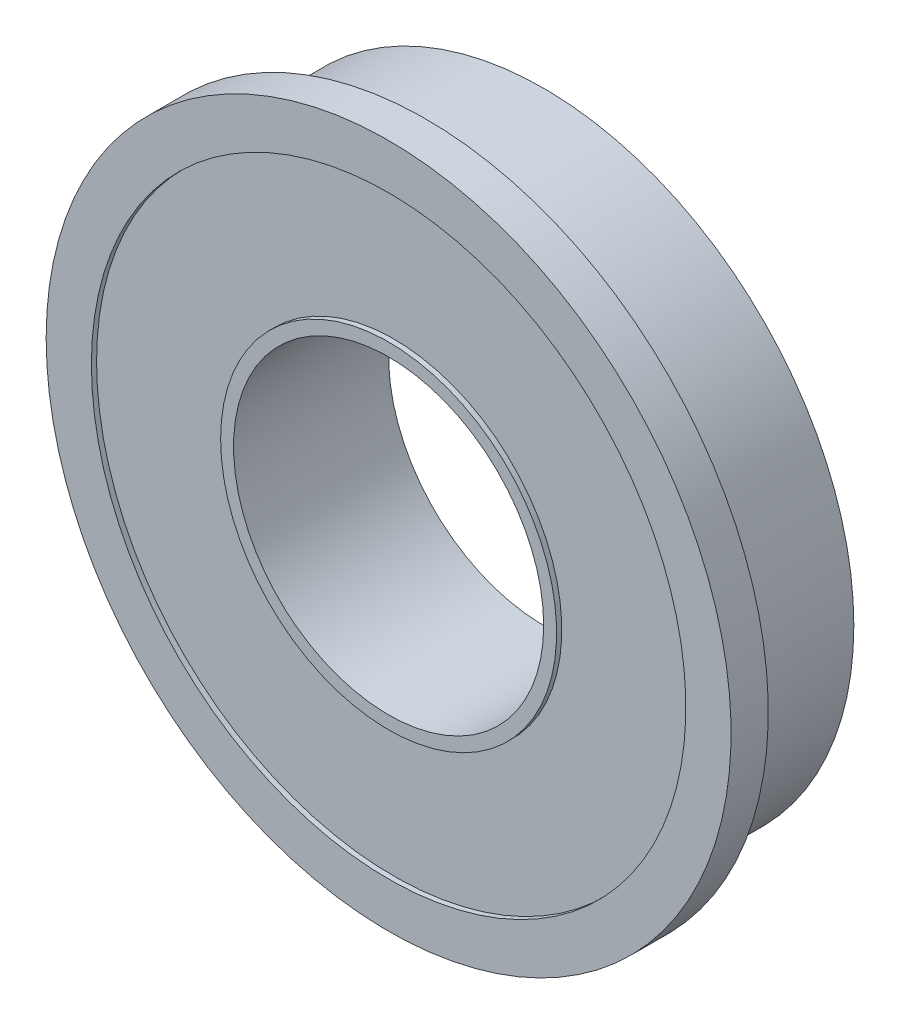
SolidWorks part; units mm, degrees
ref_plane "前视基准面" through (0, 0, 0) normal (0, 0, 1) x (1, 0, 0)
ref_plane "上视基准面" through (0, 0, 0) normal (0, 1, 0) x (1, 0, 0)
ref_plane "右视基准面" through (0, 0, 0) normal (1, 0, 0) x (0, 0, -1)
sketch "草图1" plane through (0, 0, 0) normal (0, 0, 1) x (1, 0, 0)
  circle A0 centre (0, 0) radius 12
  circle A1 centre (0, 0) radius 13.25
  dimension "D1" = 24
  dimension "D2" = 26.5
extrude "凸台-拉伸1" add sketch "草图1" along normal blind 1.44
sketch "草图2" plane through (0, 0, 1.44) normal (0, 0, 1) x (1, 0, 0)
  circle A0 centre (0, 0) radius 12
  circle A1 centre (0, 0) radius 6
  circle A3 centre (0, 0) radius 12 construction
  dimension "D2" = 12
extrude "凸台-拉伸2" add sketch "草图2" against normal blind 6
sketch "草图3" plane through (0, 0, -4.56) normal (0, 0, -1) x (-1, 0, 0)
  circle A0 centre (0, 0) radius 6.5
  circle A1 centre (0, 0) radius 11.5
  circle A2 centre (0, 0) radius 12 construction
  circle A3 centre (0, 0) radius 6 construction
  dimension "D1" = 0.5
  dimension "D2" = 0.5
extrude "切除-拉伸1" cut sketch "草图3" against normal blind 0.2
ref_plane "基准面1" through (0, 0, -1.56) normal (0, 0, -1) x (-1, 0, 0)
mirror "镜向1" about plane through (0, 0, -1.56) normal (0, 0, -1) of "切除-拉伸1"
